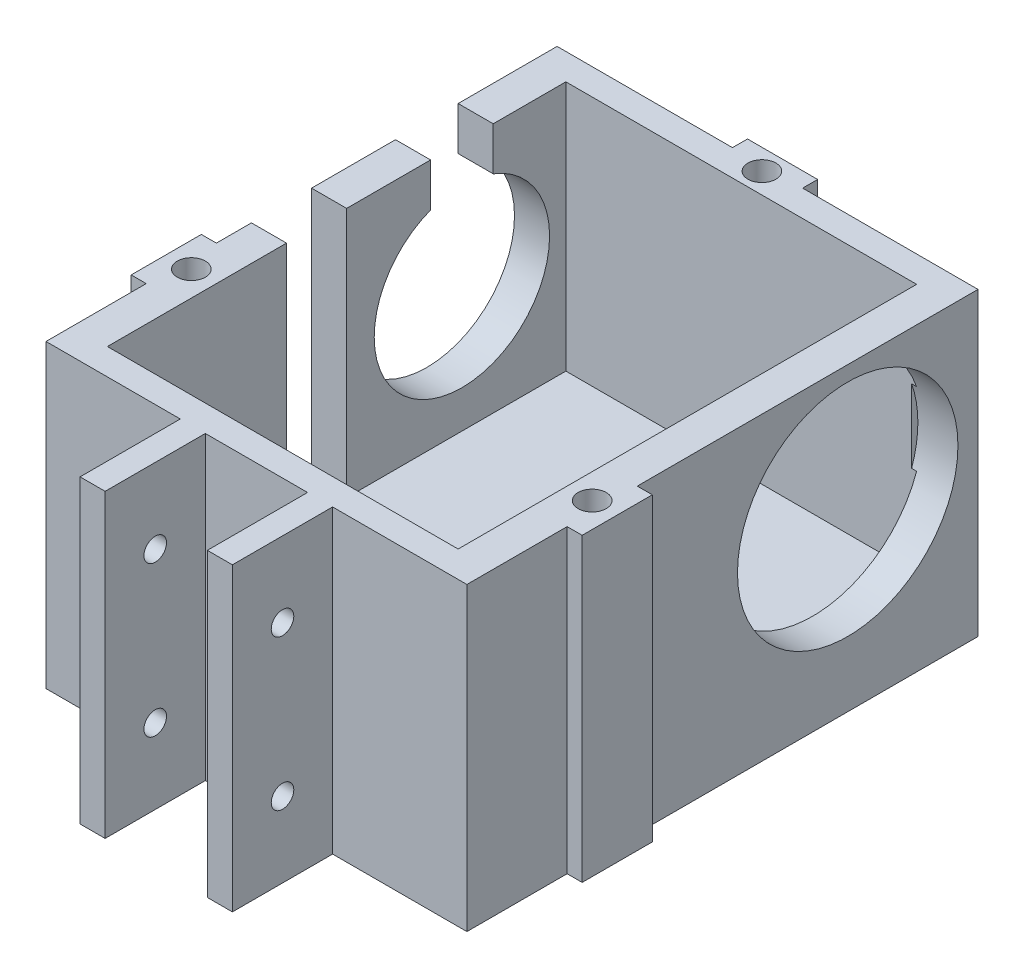
SolidWorks part; units mm, degrees
ref_plane "Front Plane" through (0, 0, 0) normal (0, 0, 1) x (1, 0, 0)
ref_plane "Top Plane" through (0, 0, 0) normal (0, 1, 0) x (1, 0, 0)
ref_plane "Right Plane" through (0, 0, 0) normal (1, 0, 0) x (0, 0, -1)
sketch "Sketch1" plane through (0, 0, 0) normal (0, 1, 0) x (1, 0, 0)
  line L1 (-21, 25.5) -> (21, 25.5)
  line L2 (-21, 25.5) -> (-21, -25.5)
  line L3 (-21, -25.5) -> (21, -25.5)
  line L4 (21, 25.5) -> (21, -25.5)
  point P4 (-21, 0)
  point P6 (0, 25.5)
  dimension "D1" = 42
  dimension "D2" = 51
extrude "Boss-Extrude1" add sketch "Sketch1" along normal blind 5 contours L4 L1 L2 L3
sketch "Sketch3" plane through (0, 5, 0) normal (0, 1, 0) x (1, 0, 0)
  line L1 (-17.5, 22.875) -> (17.5, 22.875)
  line L2 (-17.5, 22.875) -> (-17.5, -22.875)
  line L3 (-17.5, -22.875) -> (17.5, -22.875)
  line L4 (17.5, 22.875) -> (17.5, -22.875)
  line L5 (-21, 25.5) -> (21, 25.5)
  line L6 (-21, 25.5) -> (-21, -25.5)
  line L7 (-21, -25.5) -> (21, -25.5)
  line L8 (21, 25.5) -> (21, -25.5)
  point P4 (-17.5, 0)
  point P6 (0, 22.875)
  dimension "D1" = 35
  dimension "D2" = 45.75
extrude "Boss-Extrude3" add sketch "Sketch3" along normal blind 25
sketch "Sketch4" plane through (-21, 0, 0) normal (-1, 0, 0) x (0, 0, 1)
  line L1 (-25.5, 30) -> (25.5, 30) construction
  line L2 (0, 30) -> (0, 0) construction
  circle A0 centre (-12.5, 17.5) radius 8.75
  dimension "D2" = 17.5
  dimension "D1" = 12.5
  dimension "D3" = 12.5
extrude "Cut-Extrude2" cut sketch "Sketch4" against normal blind 5
sketch "Sketch6" plane through (-17.5, 0, 0) normal (1, 0, 0) x (0, 0, -1)
  line L0 (-25.5, 30) -> (25.5, 30) construction
  line L2 (0, 30) -> (0, 0) construction
  line L4 (9.375, 17.5) -> (9.375, 30)
  line L5 (9.375, 30) -> (15.625, 30)
  line L6 (15.625, 17.5) -> (15.625, 30)
  line L7 (-25.5, 30) -> (25.5, 30) construction
  arc A0 (9.375, 17.5) -> (15.625, 17.5) centre (12.5, 17.5) ccw
  point P11 (12.5, 30)
  dimension "D1" = 6.25
  dimension "D2" = 12.5
  dimension "D3" = 12.5
extrude "Cut-Extrude3" cut sketch "Sketch6" against normal blind 4
sketch "Sketch7" plane through (-21, 0, 0) normal (-1, 0, 0) x (0, 0, 1)
  line L0 (-9.375, 30) -> (25.5, 30) construction
  line L1 (-1, 30) -> (5, 30)
  line L2 (-1, 30) -> (-1, 5)
  line L3 (-1, 5) -> (5, 5)
  line L4 (5, 30) -> (5, 5)
  line L7 (-25.5, 0) -> (25.5, 0) construction
  line L8 (25.5, 30) -> (25.5, 0) construction
  dimension "D1" = 20.5
  dimension "D2" = 5
  dimension "D3" = 6
extrude "Cut-Extrude4" cut sketch "Sketch7" against normal blind 4
sketch "Sketch9" plane through (21, 0, 0) normal (1, 0, 0) x (0, 0, -1)
  line L0 (25.5, 30) -> (25.5, 0) construction
  line L1 (-25.5, 30) -> (25.5, 30) construction
  circle A0 centre (12.5, 17.5) radius 11
  dimension "D2" = 22
  dimension "D1" = 13
  dimension "D3" = 12.5
extrude "Cut-Extrude5" cut sketch "Sketch9" against normal blind 4
sketch "Sketch16" plane through (-21, 0, 0) normal (-1, 0, 0) x (0, 0, 1)
  line L0 (5, 30) -> (25.5, 30) construction
  line L1 (15.5, 30) -> (8.5, 30)
  line L2 (15.5, 30) -> (15.5, 0)
  line L3 (15.5, 0) -> (8.5, 0)
  line L4 (8.5, 30) -> (8.5, 0)
  line L5 (-25.5, 0) -> (25.5, 0) construction
  line L6 (25.5, 30) -> (25.5, 0) construction
  dimension "D1" = 10
  dimension "D2" = 7
extrude "Boss-Extrude5" add sketch "Sketch16" along normal blind 1.5
sketch "Sketch19" plane through (0, 0, -25.5) normal (0, 0, -1) x (-1, 0, 0)
  line L0 (-21, 30) -> (21, 30) construction
  line L1 (3.5, 30) -> (-3.5, 30)
  line L2 (3.5, 30) -> (3.5, 0)
  line L3 (3.5, 0) -> (-3.5, 0)
  line L4 (-3.5, 30) -> (-3.5, 0)
  line L5 (21, 0) -> (-21, 0) construction
  point P8 (0, 0)
  point P9 (0, 30)
  dimension "D1" = 7
extrude "Boss-Extrude7" add sketch "Sketch19" along normal blind 1.5
sketch "Sketch23" plane through (21, 0, 0) normal (1, 0, 0) x (0, 0, -1)
  line L0 (-25.5, 30) -> (25.5, 30) construction
  line L1 (-15.5, 30) -> (-8.5, 30)
  line L2 (-15.5, 30) -> (-15.5, 0)
  line L3 (-15.5, 0) -> (-8.5, 0)
  line L4 (-8.5, 30) -> (-8.5, 0)
  line L5 (25.5, 0) -> (-25.5, 0) construction
  line L6 (-25.5, 30) -> (-25.5, 0) construction
  dimension "D1" = 7
  dimension "D2" = 10
extrude "Boss-Extrude11" add sketch "Sketch23" along normal blind 1.5
sketch "Sketch18" plane through (0, 30, 0) normal (0, 1, 0) x (1, 0, 0)
  line L0 (-22.5, -15.5) -> (-22.5, -8.5) construction
  line L1 (0, -19.5533) -> (0, 11.7982) construction
  line L2 (-3.5, 27) -> (3.5, 27) construction
  line L3 (-22.5, -12) -> (-17.5, -12) construction
  line L4 (-17.5, -5) -> (-17.5, -22.875) construction
  line L5 (0, 27) -> (0, 22.875) construction
  line L6 (17.5, 22.875) -> (-17.5, 22.875) construction
  circle A0 centre (-20, -12) radius 1.4
  circle A2 centre (0, 24.9375) radius 1.4
  circle A3 centre (20, -12) radius 1.4
  point P5 (-22.5, -12)
  point P17 (0, 27)
  point P21 (-20, -12)
  point P26 (0, 24.9375)
  dimension "D1" = 2.8
extrude "Cut-Extrude7" cut sketch "Sketch18" against normal blind 6
sketch "Sketch20" plane through (0, 0, 25.5) normal (0, 0, 1) x (1, 0, 0)
  line L6 (-21, 30) -> (21, 30) construction
  line L7 (0, 0) -> (0, 30) construction
  line L8 (-5.1, 0) -> (-7.6, 0)
  line L9 (-5.1, 0) -> (-5.1, 30)
  line L10 (-5.1, 30) -> (-7.6, 30)
  line L11 (-7.6, 0) -> (-7.6, 30)
  line L12 (5.1, 30) -> (7.6, 30)
  line L13 (7.6, 0) -> (7.6, 30)
  line L14 (5.1, 0) -> (7.6, 0)
  line L15 (5.1, 0) -> (5.1, 30)
  dimension "D1" = 2.5
  dimension "D2" = 5.1
extrude "Boss-Extrude10" add sketch "Sketch20" along normal blind 10
sketch "Sketch22" plane through (-7.6, 0, 0) normal (-1, 0, 0) x (0, 0, 1)
  line L0 (35.5, 15) -> (25.5, 15) construction
  line L1 (35.5, 30) -> (35.5, 0) construction
  line L2 (25.5, 30) -> (25.5, 0) construction
  line L3 (30.5, 15) -> (30.5, 30) construction
  line L4 (35.5, 30) -> (25.5, 30) construction
  circle A0 centre (30.5, 22.5) radius 1.125
  circle A1 centre (30.5, 7.5) radius 1.125
  dimension "D1" = 2.25
extrude "Cut-Extrude8" cut sketch "Sketch22" against normal blind 20
